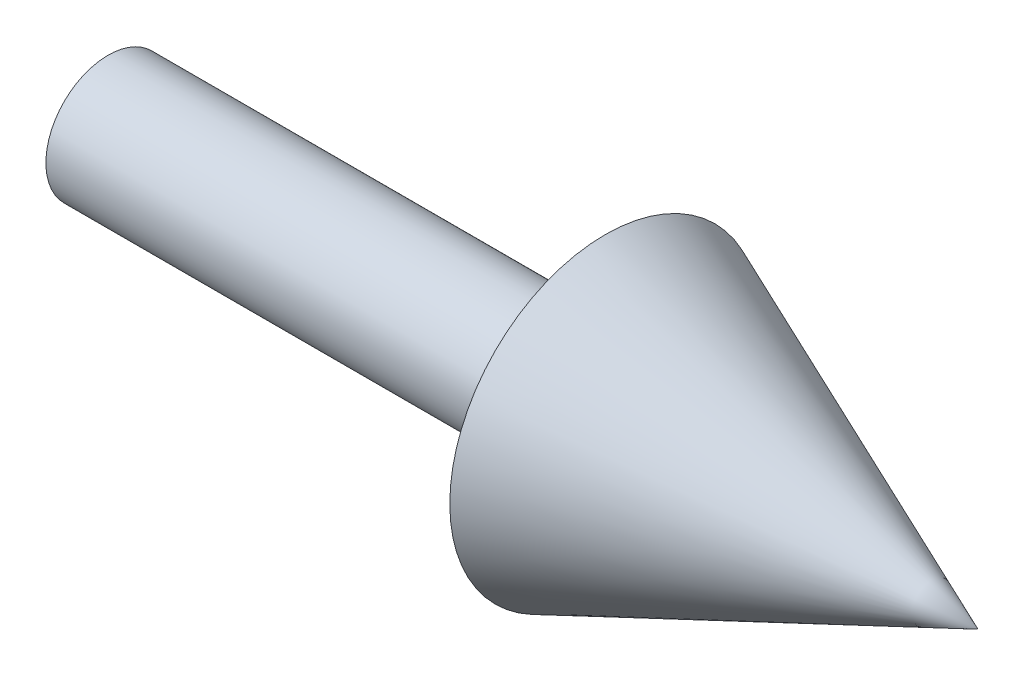
SolidWorks part; units mm, degrees
ref_plane "Front Plane" through (0, 0, 0) normal (0, 0, 1) x (1, 0, 0)
ref_plane "Top Plane" through (0, 0, 0) normal (0, 1, 0) x (1, 0, 0)
ref_plane "Right Plane" through (0, 0, 0) normal (1, 0, 0) x (0, 0, -1)
sketch "Sketch1" plane through (0, 0, 0) normal (0, 0, 1) x (1, 0, 0)
  line L0 (0, 0) -> (-10.2712, 0) construction
  line L1 (0, 0) -> (0, 5)
  line L2 (0, 5) -> (40, 5)
  line L3 (40, 5) -> (40, 12.5)
  line L4 (40, 12.5) -> (70, 0)
  line L5 (70, 0) -> (0, 0)
  dimension "D1" = 70
  dimension "D2" = 10
  dimension "D3" = 30
  dimension "D4" = 25
revolve "Revolve1" add sketch "Sketch1" angle 360 about L0
